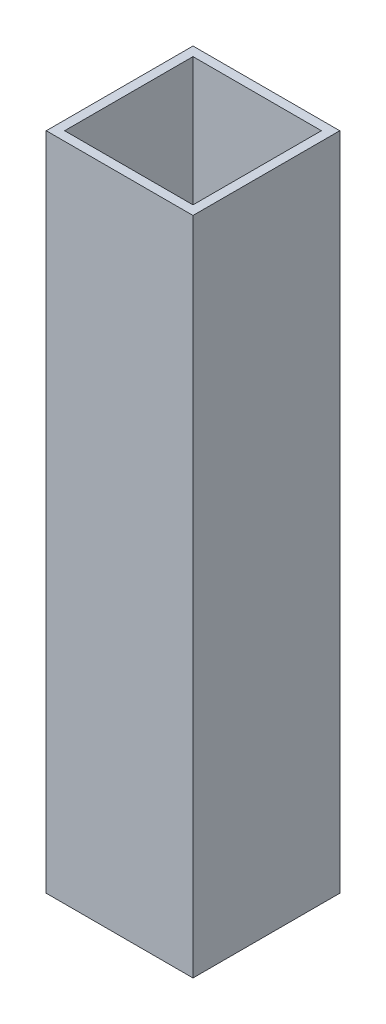
SolidWorks part; units mm, degrees
material "6061 Alloy"
ref_plane "Front Plane" through (0, 0, 0) normal (0, 0, 1) x (1, 0, 0)
ref_plane "Top Plane" through (0, 0, 0) normal (0, 1, 0) x (1, 0, 0)
ref_plane "Right Plane" through (0, 0, 0) normal (1, 0, 0) x (0, 0, -1)
sketch "Sketch1" plane through (0, 0, 0) normal (0, 1, 0) x (1, 0, 0)
  line L1 (12.7, -12.7) -> (-12.7, -12.7)
  line L2 (12.7, -12.7) -> (12.7, 12.7)
  line L3 (12.7, 12.7) -> (-12.7, 12.7)
  line L4 (-12.7, -12.7) -> (-12.7, 12.7)
  line L5 (12.7, -12.7) -> (-12.7, 12.7) construction
  line L6 (12.7, 12.7) -> (-12.7, -12.7) construction
  line L7 (11.1125, -11.1125) -> (-11.1125, -11.1125)
  line L8 (11.1125, -11.1125) -> (11.1125, 11.1125)
  line L9 (11.1125, 11.1125) -> (-11.1125, 11.1125)
  line L10 (-11.1125, -11.1125) -> (-11.1125, 11.1125)
  line L11 (11.1125, -11.1125) -> (-11.1125, 11.1125) construction
  line L12 (11.1125, 11.1125) -> (-11.1125, -11.1125) construction
  point P0 (0, 0)
  point P6 (0, 0)
  dimension "D1" = 25.4
  dimension "D2" = 25.4
  dimension "D3" = 1.5875
extrude "Boss-Extrude1" add sketch "Sketch1" along normal blind 114.3
